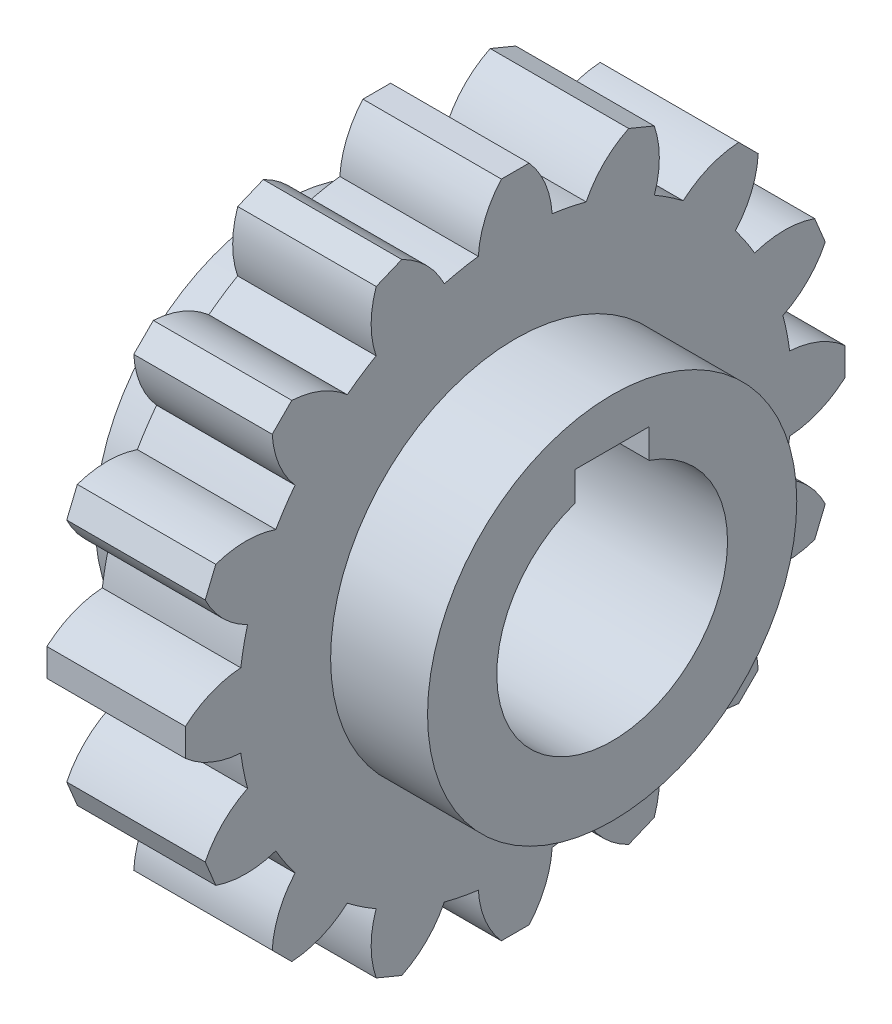
SolidWorks part; units mm, degrees
material "AISI 4130 Steel, normalized at 870C"
ref_plane "Front Plane" through (0, 0, 0) normal (0, 0, 1) x (1, 0, 0)
ref_plane "Top Plane" through (0, 0, 0) normal (0, 1, 0) x (1, 0, 0)
ref_plane "Right Plane" through (0, 0, 0) normal (1, 0, 0) x (0, 0, -1)
sketch "Sketch1" plane through (0, 0, 0) normal (1, 0, 0) x (0, 0, -1)
  circle A1 centre (0, 0) radius 30
  dimension "D1" = 60
extrude "Boss-Extrude1" add sketch "Sketch1" along normal mid plane 15
sketch "Sketch2" plane through (7.5, 0, 0) normal (1, 0, 0) x (0, 0, -1)
  line L0 (0, 0) -> (0, 35.7321) construction
  line L1 (-1.5, 35.7321) -> (1.5, 35.7321)
  arc A0 (-4, 29.7321) -> (4, 29.7321) centre (0, 0) cw
  circle A1 centre (0, 0) radius 30 construction
  arc A2 (1.5, 35.7321) -> (4, 29.7321) centre (-5.9797, 29.0948) cw
  arc A3 (-1.5, 35.7321) -> (-4, 29.7321) centre (5.9797, 29.0948) ccw
  dimension "D4" = 10
  dimension "D1" = 1.5
  dimension "D2" = 4
  dimension "D3" = 6
extrude "Boss-Extrude2" add sketch "Sketch2" against normal up to surface (15 mm away) up to face at (-7.5, 0, -30)
pattern_circular "CirPattern1" count 16 over 360 about axis through (0, 0, 0) along (1, 0, 0) of "Boss-Extrude2"
sketch "Sketch3" plane through (0, 0, 0) normal (1, 0, 0) x (0, 0, -1)
  circle A0 centre (0, 0) radius 20
  dimension "D1" = 40
extrude "Boss-Extrude3" add sketch "Sketch3" along normal mid plane 36
sketch "Sketch4" plane through (18, 0, 0) normal (1, 0, 0) x (0, 0, -1)
  line L0 (0, 0) -> (0, 15) construction
  line L1 (-4, 15) -> (4, 15)
  line L2 (-4, 15) -> (-4, 11.8427)
  line L3 (4, 15) -> (4, 11.8427)
  arc A0 (-4, 11.8427) -> (4, 11.8427) centre (0, 0) ccw
  dimension "D1" = 25
  dimension "D2" = 8
  dimension "D3" = 15
extrude "Cut-Extrude1" cut sketch "Sketch4" against normal through all
